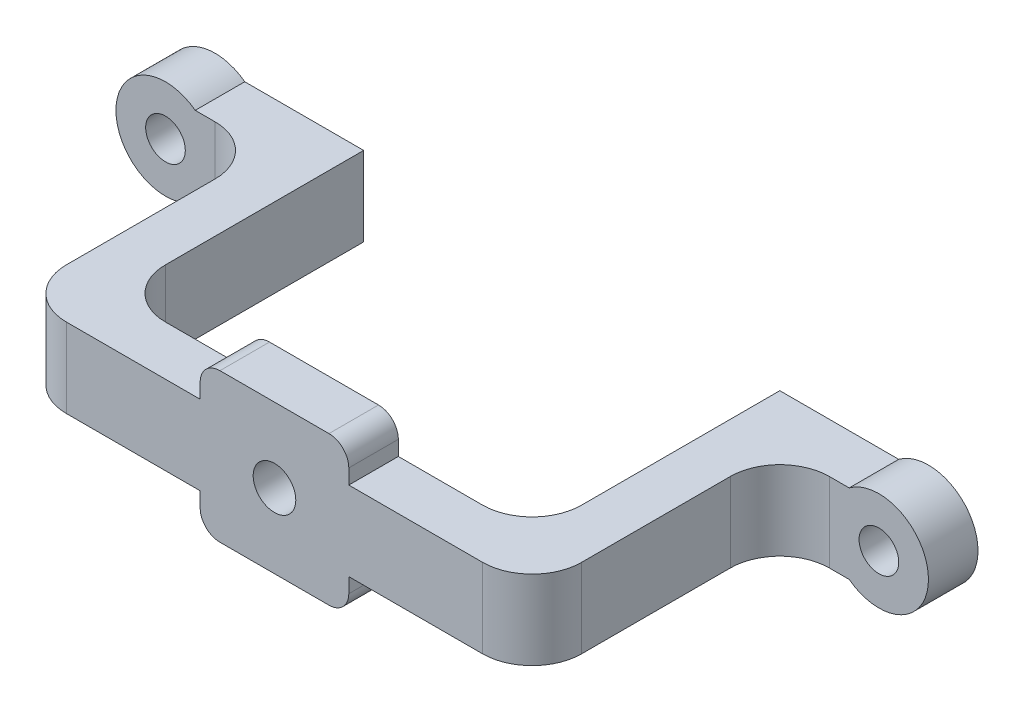
SolidWorks part; units mm, degrees
ref_plane "前视基准面" through (0, 0, 0) normal (0, 0, 1) x (1, 0, 0)
ref_plane "上视基准面" through (0, 0, 0) normal (0, 1, 0) x (1, 0, 0)
ref_plane "右视基准面" through (0, 0, 0) normal (1, 0, 0) x (0, 0, -1)
other "Configuration Table"
sketch "草图1" plane through (0, 0, 0) normal (0, 0, 1) x (1, 0, 0)
  circle A0 centre (0, 0) radius 5
  dimension "D1" = 10
extrude "凸台-拉伸1" add sketch "草图1" along normal blind 5
sketch "草图3" plane through (0, 0, 0) normal (1, 0, 0) x (0, 0, -1)
  line L0 (0, -5) -> (0, 5) construction
  line L1 (0, 4) -> (-5, 4)
  line L2 (0, 4) -> (0, -4)
  line L3 (0, -4) -> (-5, -4)
  line L4 (-5, 4) -> (-5, -4)
  line L5 (-5, 0) -> (0, 0) construction
  dimension "D1" = 5
  dimension "D2" = 8
  dimension "D3" = 4
extrude "凸台-拉伸2" add sketch "草图3" along normal blind 15
sketch "草图2" plane through (0, 0, 5) normal (0, 0, 1) x (1, 0, 0)
  circle A0 centre (0, 0) radius 2
  dimension "D1" = 4
extrude "切除-拉伸1" cut sketch "草图2" against normal blind 30
sketch "草图6" plane through (0, 0, 5) normal (0, 0, 1) x (1, 0, 0)
  line L0 (15, -4) -> (3, -4) construction
  line L1 (15, 4) -> (10, 4)
  line L2 (15, 4) -> (15, -4)
  line L3 (15, -4) -> (10, -4)
  line L4 (10, 4) -> (10, -4)
  dimension "D1" = 5
extrude "凸台-拉伸4" add sketch "草图6" along normal blind 25
sketch "草图7" plane through (15, 0, 0) normal (1, 0, 0) x (0, 0, -1)
  line L0 (-30, -4) -> (0, -4) construction
  line L1 (-30, 4) -> (-25, 4)
  line L2 (-30, 4) -> (-30, -4)
  line L3 (-30, -4) -> (-25, -4)
  line L4 (-25, 4) -> (-25, -4)
  dimension "D1" = 5
extrude "凸台-拉伸5" add sketch "草图7" along normal blind 21
mirror "镜向2" about plane through (36, 0, 0) normal (1, 0, 0) of bodies 123
sketch "草图8" plane through (0, 0, 30) normal (0, 0, 1) x (1, 0, 0)
  line L0 (36, 4) -> (36, -4) construction
  line L1 (62, 4) -> (10, 4) construction
  line L2 (10, -4) -> (62, -4) construction
  line L3 (36, 0) -> (40.108, 0) construction
  line L5 (28.5, 7.5) -> (43.5, 7.5)
  line L6 (28.5, 7.5) -> (28.5, -7.5)
  line L7 (28.5, -7.5) -> (43.5, -7.5)
  line L8 (43.5, 7.5) -> (43.5, -7.5)
  dimension "D1" = 15
  dimension "D2" = 15
  dimension "D3" = 7.5
  dimension "D4" = 7.5
extrude "凸台-拉伸6" add sketch "草图8" against normal up to surface (5 mm away) up to face at (36, 0, 25)
fillet "圆角2" radius 2 4 edges at (43.5, -7.5, 27.5) (28.5, -7.5, 27.5) (28.5, 7.5, 27.5) (43.5, 7.5, 27.5)
sketch "草图9" plane through (0, 0, 30) normal (0, 0, 1) x (1, 0, 0)
  line L0 (36, 7.5) -> (36, -7.5) construction
  line L1 (41.5, 7.5) -> (30.5, 7.5) construction
  line L2 (30.5, -7.5) -> (41.5, -7.5) construction
  circle A0 centre (36, 0) radius 2.15
  dimension "D1" = 4.3
extrude "切除-拉伸2" cut sketch "草图9" against normal blind 10
fillet "圆角3" radius 5 6 edges at (10, 0, 5) (62, 0, 5) (62, 0, 30) (10, 0, 30) (57, 0, 25) (15, 0, 25)
